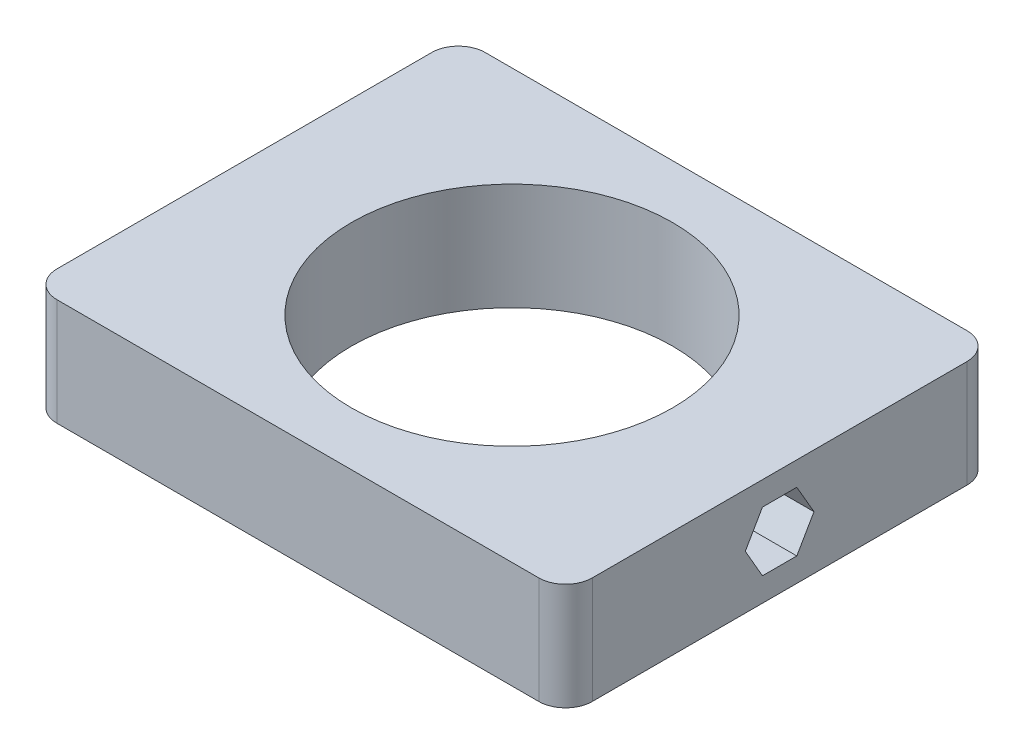
SolidWorks part; units mm, degrees
ref_plane "Front Plane" through (0, 0, 0) normal (0, 0, 1) x (1, 0, 0)
ref_plane "Top Plane" through (0, 0, 0) normal (0, 1, 0) x (1, 0, 0)
ref_plane "Right Plane" through (0, 0, 0) normal (1, 0, 0) x (0, 0, -1)
sketch "Sketch1" plane through (0, 0, 0) normal (0, 1, 0) x (1, 0, 0)
  line L0 (-63.5, 50.8) -> (63.5, -50.8) construction
  line L1 (-57.15, 50.8) -> (57.15, 50.8)
  line L2 (-63.5, 44.45) -> (-63.5, -44.45)
  line L3 (-57.15, -50.8) -> (57.15, -50.8)
  line L4 (63.5, 44.45) -> (63.5, -44.45)
  arc A0 (57.15, 50.8) -> (63.5, 44.45) centre (57.15, 44.45) cw
  arc A1 (-63.5, -44.45) -> (-57.15, -50.8) centre (-57.15, -44.45) ccw
  arc A2 (57.15, -50.8) -> (63.5, -44.45) centre (57.15, -44.45) ccw
  arc A3 (-57.15, 50.8) -> (-63.5, 44.45) centre (-57.15, 44.45) ccw
  circle A4 centre (0, 0) radius 38.1
  dimension "D1" = 6.35
  dimension "D4" = 76.2
  dimension "D2" = 127
  dimension "D3" = 101.6
extrude "Boss-Extrude1" add sketch "Sketch1" along normal blind 25.4
sketch "Sketch2" plane through (63.5, 0, 0) normal (1, 0, 0) x (0, 0, -1)
  line L0 (0, 0) -> (0, 25.4) construction
  line L1 (-44.45, 25.4) -> (44.45, 25.4) construction
  line L3 (8.1464, 12.7) -> (4.0732, 19.755)
  line L4 (4.0732, 19.755) -> (-4.0732, 19.755)
  line L5 (-4.0732, 19.755) -> (-8.1464, 12.7)
  line L6 (-8.1464, 12.7) -> (-4.0732, 5.645)
  line L7 (-4.0732, 5.645) -> (4.0732, 5.645)
  line L8 (4.0732, 5.645) -> (8.1464, 12.7)
  circle A0 centre (0, 12.7) radius 7.055 construction
extrude "Cut-Extrude1" cut sketch "Sketch2" against normal up to next
sketch "Sketch3" plane through (0, 0, -50.8) normal (0, 0, -1) x (-1, 0, 0)
  line L0 (0, 0) -> (0, 22.3275) construction
  line L1 (0, 22.3275) -> (10.5903, 3.9845)
  line L2 (10.5903, 3.9845) -> (-10.5903, 3.9845)
  line L3 (-10.5903, 3.9845) -> (0, 22.3275)
  point P3 (0, 3.9845)
extrude "Cut-Extrude3" cut sketch "Sketch3" against normal blind 6.35
